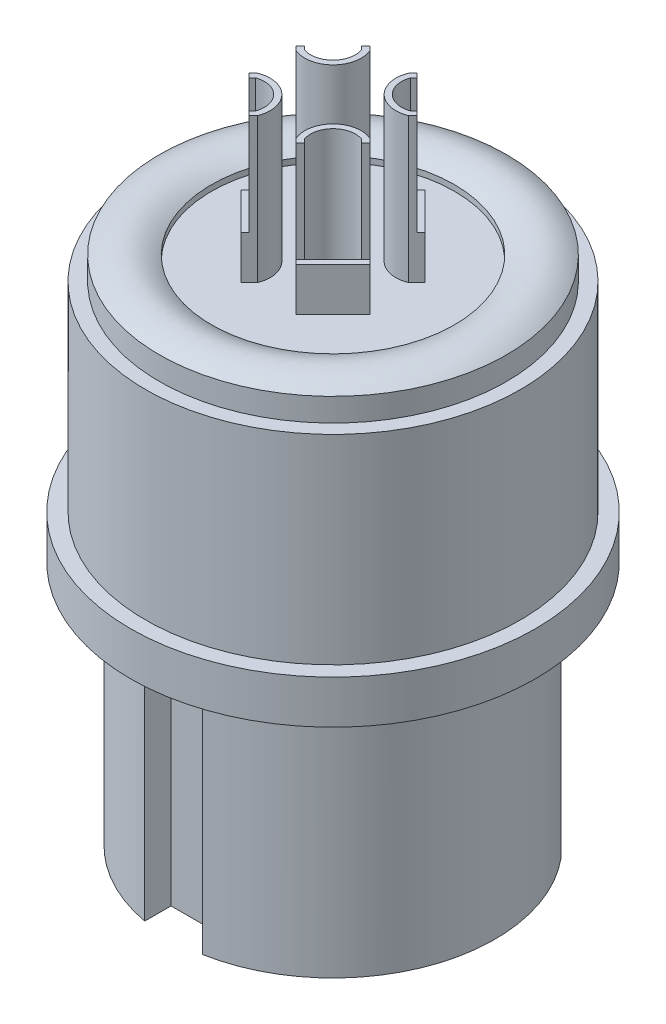
SolidWorks part; units mm, degrees
ref_plane "Спереди (Плоскость XY)" through (0, 0, 0) normal (0, 0, 1) x (1, 0, 0)
ref_plane "Сверху (Плоскость XZ)" through (0, 0, 0) normal (0, 1, 0) x (1, 0, 0)
ref_plane "Справа (Плоскость ZY)" through (0, 0, 0) normal (1, 0, 0) x (0, 0, -1)
sketch "Эскиз2" plane through (0, 0, 0) normal (0, 0, 1) x (1, 0, 0)
  line L0 (0, -18.016) -> (0, 15.4911) construction
  line L1 (0, 9.4025) -> (-4.2, 9.4025)
  line L2 (-4.2, 9.4025) -> (-4.2, 9.6025)
  line L4 (-6, 9.6025) -> (-6, 8.8025)
  line L5 (-6, 8.8025) -> (-6.48, 8.8025)
  line L6 (-6.48, 8.8025) -> (-6.48, 1.9025)
  line L7 (-6.48, 1.9025) -> (-7, 1.9025)
  line L8 (-7, 1.9025) -> (-7, 0.4025)
  line L9 (-7, 0.4025) -> (-6.52, 0.4025)
  line L10 (-6.52, 0.4025) -> (-6.52, 1.0025)
  line L11 (-6.52, 1.0025) -> (-5.6, 1.0025)
  line L12 (-5.6, 1.0025) -> (-5.6, -8.0975)
  line L13 (-5.6, -8.0975) -> (-4.5, -8.0975)
  line L14 (-4.5, -8.0975) -> (-4.5, 0.0025)
  line L15 (-4.5, 0.0025) -> (0, 0.0025)
  line L16 (0, 9.4025) -> (0, 0.0025)
  circle A0 centre (-6.06, 0.5425) radius 0.45
  spline S0 degree 2 poles (-6, 9.6025) (-5.1, 10.2025) (-4.2, 9.6025) knots 0 0 0 1 1 1
  point P23 (-5.61, 0.5425)
  point P24 (-6.06, 0.9925)
  point P25 (-6.51, 0.5425)
  dimension "D14" = 0.9
  dimension "D15" = 0.01
  dimension "D1" = 4.2
  dimension "D2" = 0.2
  dimension "D3" = 6
  dimension "D4" = 0.5
  dimension "D5" = 6.48
  dimension "D6" = 0.8
  dimension "D7" = 7
  dimension "D8" = 8.5
  dimension "D9" = 18
  dimension "D10" = 8.1
  dimension "D11" = 1.5
  dimension "D12" = 0.6
  dimension "D13" = 0.92
  dimension "D16" = 0.01
  dimension "D17" = 5.6
  dimension "D18" = 4.5
revolve "Повернуть1" add sketch "Эскиз2" angle 360 about L0
sketch "Эскиз3" plane through (0, 9.4025, 0) normal (0, 1, 0) x (1, 0, 0)
  line L0 (0, 0) -> (0, 2.8233) construction
  line L1 (0, 0) -> (1.9801, 1.9801) construction
  line L2 (0.9546, 2.2274) -> (2.2274, 0.9546)
  line L3 (0.9546, 2.2274) -> (0.6718, 1.9445)
  line L4 (2.2274, 0.9546) -> (1.9445, 0.6718)
  line L5 (0.9546, 1.9445) -> (0.8432, 1.8331)
  line L6 (1.9445, 0.9546) -> (1.8331, 0.8432)
  line L7 (0.9546, 1.9445) -> (1.9445, 0.9546)
  line L8 (2.2274, -0.9546) -> (1.9445, -0.6718)
  line L9 (2.2274, -0.9546) -> (0.9546, -2.2274)
  line L10 (1.9445, -0.9546) -> (0.9546, -1.9445)
  line L11 (1.9445, -0.9546) -> (1.8331, -0.8432)
  line L12 (0.9546, -1.9445) -> (0.8432, -1.8331)
  line L13 (0.9546, -2.2274) -> (0.6718, -1.9445)
  line L14 (-0.9546, -2.2274) -> (-0.6718, -1.9445)
  line L15 (-0.9546, -2.2274) -> (-2.2274, -0.9546)
  line L16 (-0.9546, -1.9445) -> (-1.9445, -0.9546)
  line L17 (-0.9546, -1.9445) -> (-0.8432, -1.8331)
  line L18 (-1.9445, -0.9546) -> (-1.8331, -0.8432)
  line L19 (-2.2274, -0.9546) -> (-1.9445, -0.6718)
  line L20 (-2.2274, 0.9546) -> (-1.9445, 0.6718)
  line L21 (-2.2274, 0.9546) -> (-0.9546, 2.2274)
  line L22 (-1.9445, 0.9546) -> (-0.9546, 1.9445)
  line L23 (-1.9445, 0.9546) -> (-1.8331, 0.8432)
  line L24 (-0.9546, 1.9445) -> (-0.8432, 1.8331)
  line L25 (-0.9546, 2.2274) -> (-0.6718, 1.9445)
  circle A0 centre (0, 0) radius 2.25 construction
  arc A1 (0.6718, 1.9445) -> (1.9445, 0.6718) centre (1.5733, 1.5733) ccw
  arc A2 (0.8432, 1.8331) -> (1.8331, 0.8432) centre (1.5733, 1.5733) ccw
  arc A3 (1.9445, -0.6718) -> (0.6718, -1.9445) centre (1.5733, -1.5733) ccw
  arc A4 (1.8331, -0.8432) -> (0.8432, -1.8331) centre (1.5733, -1.5733) ccw
  arc A5 (-0.6718, -1.9445) -> (-1.9445, -0.6718) centre (-1.5733, -1.5733) ccw
  arc A6 (-0.8432, -1.8331) -> (-1.8331, -0.8432) centre (-1.5733, -1.5733) ccw
  arc A7 (-1.9445, 0.6718) -> (-0.6718, 1.9445) centre (-1.5733, 1.5733) ccw
  arc A8 (-1.8331, 0.8432) -> (-0.8432, 1.8331) centre (-1.5733, 1.5733) ccw
  point P7 (1.591, 1.591)
  point P8 (0.8839, 0.8839)
  point P12 (0.8839, 0.8839)
  point P51 (0, 0)
  dimension "D1" = 4.5
  dimension "D6" = 0.2
  dimension "D2" = 45
  dimension "D3" = 1.8
  dimension "D4" = 0.4
  dimension "D5" = 1
  dimension "D7" = 4
extrude "Бобышка-Вытянуть1" add sketch "Эскиз3" along normal blind 5
sketch "Эскиз4" plane through (0, 14.4025, 0) normal (0, 1, 0) x (1, 0, 0)
  line L0 (0, -2.8991) -> (2.8991, 0)
  line L1 (0, -2.8991) -> (-2.8991, 0)
  line L2 (2.8991, 0) -> (0, 2.8991)
  line L3 (-2.8991, 0) -> (0, 2.8991)
  line L4 (0, -2.8991) -> (0, 2.8991) construction
  line L5 (2.8991, 0) -> (-2.8991, 0) construction
  line L6 (-0.9546, 1.9445) -> (-1.9445, 0.9546) construction
  line L7 (1.9445, 0.9546) -> (0.9546, 1.9445) construction
  circle A0 centre (0, 0) radius 3.6662
  point P1 (0, 0)
extrude "Вырез-Вытянуть1" cut sketch "Эскиз4" against normal blind 3.5
sketch "Эскиз5" plane through (0, 0.0025, 0) normal (0, -1, 0) x (1, 0, 0)
  line L0 (0, 3.8833) -> (0, 0) construction
  line L1 (0, 0) -> (1.9977, 1.9977) construction
  circle A0 centre (0, 0) radius 2.25 construction
  circle A1 centre (1.591, 1.591) radius 0.495
  circle A2 centre (1.591, -1.591) radius 0.495
  circle A3 centre (-1.591, -1.591) radius 0.495
  circle A4 centre (-1.591, 1.591) radius 0.495
  point P16 (0, 0)
  dimension "D1" = 4.5
  dimension "D3" = 0.99
  dimension "D2" = 45
extrude "Бобышка-Вытянуть2" add sketch "Эскиз5" along normal offset from surface (6.6 mm away) 1.5 up to face at (0, -8.0975, -4.5)
sketch "Эскиз6" plane through (0, -8.0975, 0) normal (0, -1, 0) x (1, 0, 0)
  line L0 (0, 0) -> (0, 4.6) construction
  line L1 (-1, 4.6) -> (1, 4.6)
  line L2 (-1, 4.6) -> (-1, 6.6)
  line L3 (1, 4.6) -> (1, 6.6)
  line L4 (0, 0) -> (1.591, -1.591) construction
  line L5 (1.591, -1.591) -> (5.1998, -5.1998) construction
  line L6 (0, 0) -> (-1.591, -1.591) construction
  line L7 (-1.591, -1.591) -> (-3.2527, -3.2527) construction
  line L8 (-3.6062, -2.8991) -> (-2.8991, -3.6062)
  line L9 (-2.8991, -3.6062) -> (-4.3534, -5.0605)
  line L10 (-3.6062, -2.8991) -> (-5.0605, -4.3534)
  line L11 (2.8991, -3.6062) -> (4.3534, -5.0605)
  line L12 (3.6062, -2.8991) -> (2.8991, -3.6062)
  line L13 (3.6062, -2.8991) -> (5.0605, -4.3534)
  circle A0 centre (0, 0) radius 5.6 construction
  arc A1 (-4.3534, -5.0605) -> (4.3534, -5.0605) centre (0, 0) ccw
  circle A2 centre (0, 0) radius 9.0649
  arc A3 (5.0605, -4.3534) -> (1, 6.6) centre (0, 0) ccw
  arc A4 (-1, 6.6) -> (-5.0605, -4.3534) centre (0, 0) ccw
  point P5 (0, 4.6)
  point P10 (0, 5.6)
  point P21 (-3.2527, -3.2527)
  point P22 (-3.2527, -3.2527)
  point P23 (-3.2527, -3.2527)
  point P24 (-3.9598, -3.9598)
  dimension "D2" = 1
  dimension "D4" = 1
  dimension "D1" = 2
  dimension "D3" = 2
  dimension "D5" = 1
extrude "Вырез-Вытянуть2" cut sketch "Эскиз6" against normal blind 8
